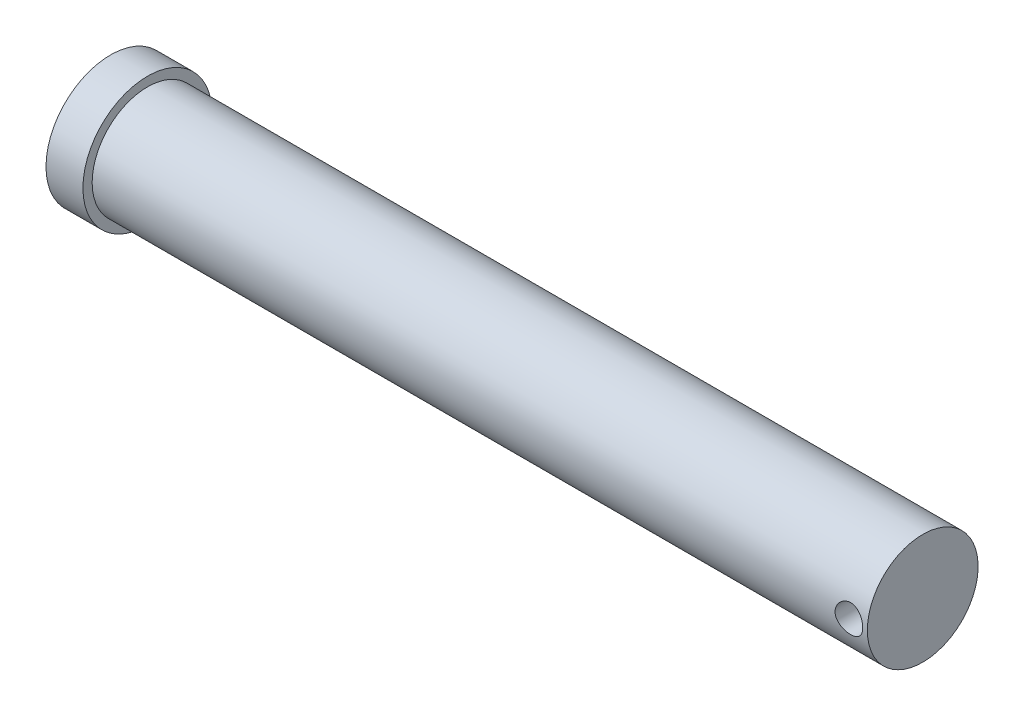
SolidWorks part; units mm, degrees
material "AISI 1020"
ref_plane "Ön Düzlem" through (0, 0, 0) normal (0, 0, 1) x (1, 0, 0)
ref_plane "Üst Düzlem" through (0, 0, 0) normal (0, 1, 0) x (1, 0, 0)
ref_plane "Sağ Düzlem" through (0, 0, 0) normal (1, 0, 0) x (0, 0, -1)
sketch "Çizim1" plane through (0, 0, 0) normal (0, 0, 1) x (1, 0, 0)
  line L0 (0, 0) -> (440, 0) construction
  line L1 (0, 0) -> (0, 35)
  line L2 (0, 35) -> (20, 35)
  line L3 (20, 35) -> (20, 30)
  line L4 (20, 30) -> (440, 30)
  line L5 (440, 30) -> (440, 0)
  line L6 (0, 0) -> (440, 0)
  dimension "D1" = 440
  dimension "D2" = 20
  dimension "D3" = 5
  dimension "D4" = 30
revolve "Döndür1" add sketch "Çizim1" angle 360 about L0
sketch "Çizim2" plane through (0, 0, 0) normal (0, 0, 1) x (1, 0, 0)
  line L0 (440, -30) -> (440, 30) construction
  circle A0 centre (430, 0) radius 7.5
  dimension "D2" = 15
  dimension "D1" = 10
extrude "Kes-Ekstrüzyon1" cut sketch "Çizim2" against normal mid plane 60
